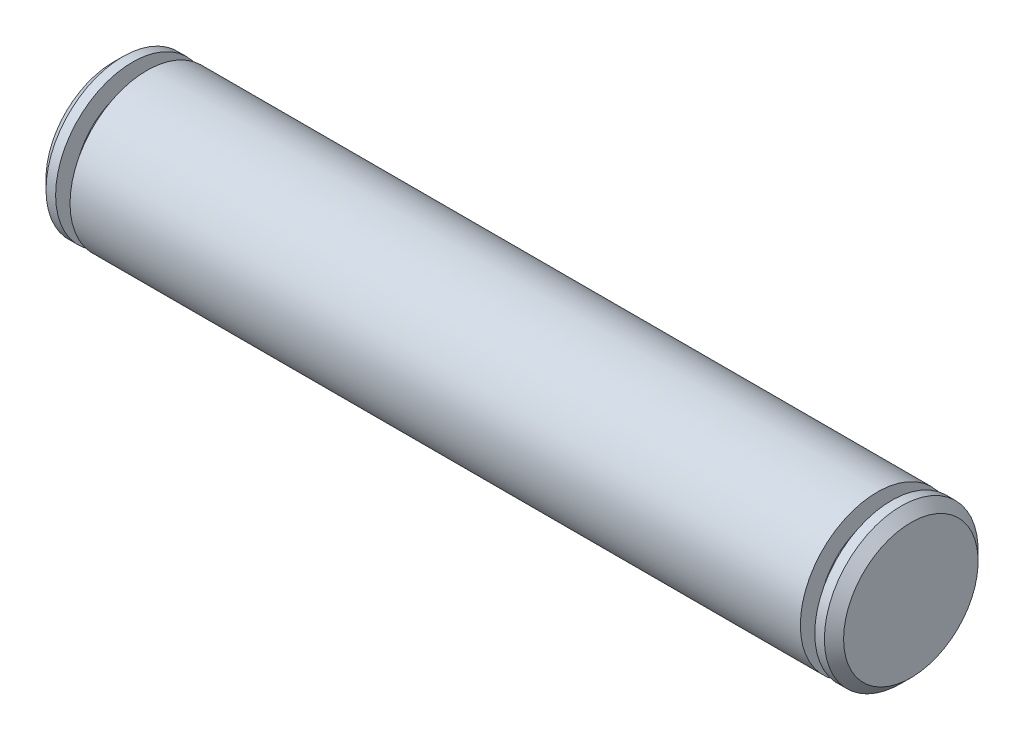
SolidWorks part; units mm, degrees
material "Plain Carbon Steel"
ref_plane "Front Plane" through (0, 0, 0) normal (0, 0, 1) x (1, 0, 0)
ref_plane "Top Plane" through (0, 0, 0) normal (0, 1, 0) x (1, 0, 0)
ref_plane "Right Plane" through (0, 0, 0) normal (1, 0, 0) x (0, 0, -1)
sketch "Sketch1" plane through (0, 0, 0) normal (0, 0, 1) x (1, 0, 0)
  line L0 (-41.5, 0) -> (-41.5, 8)
  line L1 (-41.5, 0) -> (41.5, 0)
  line L2 (-41.5, 8) -> (-39.5, 8)
  line L3 (-39.5, 8) -> (-39.5, 6)
  line L4 (-39.5, 6) -> (-38, 6)
  line L5 (-38, 6) -> (-38, 8)
  line L6 (-38, 8) -> (38, 8)
  line L7 (-47.152, 0) -> (-41.5, 0) construction
  line L8 (0, 8) -> (0, 0) construction
  line L9 (38, 6) -> (38, 8)
  line L10 (39.5, 6) -> (38, 6)
  line L11 (39.5, 8) -> (39.5, 6)
  line L12 (41.5, 8) -> (39.5, 8)
  line L13 (41.5, 0) -> (41.5, 8)
  dimension "D1" = 16
  dimension "D2" = 76
  dimension "D3" = 1.5
  dimension "D4" = 12
  dimension "D5" = 2
revolve "Revolve1" add sketch "Sketch1" angle 360 about L7
chamfer "Chamfer1" distance 1 angle 45 2 edges at (41.5, 0, 8) (-41.5, 0, 8)
